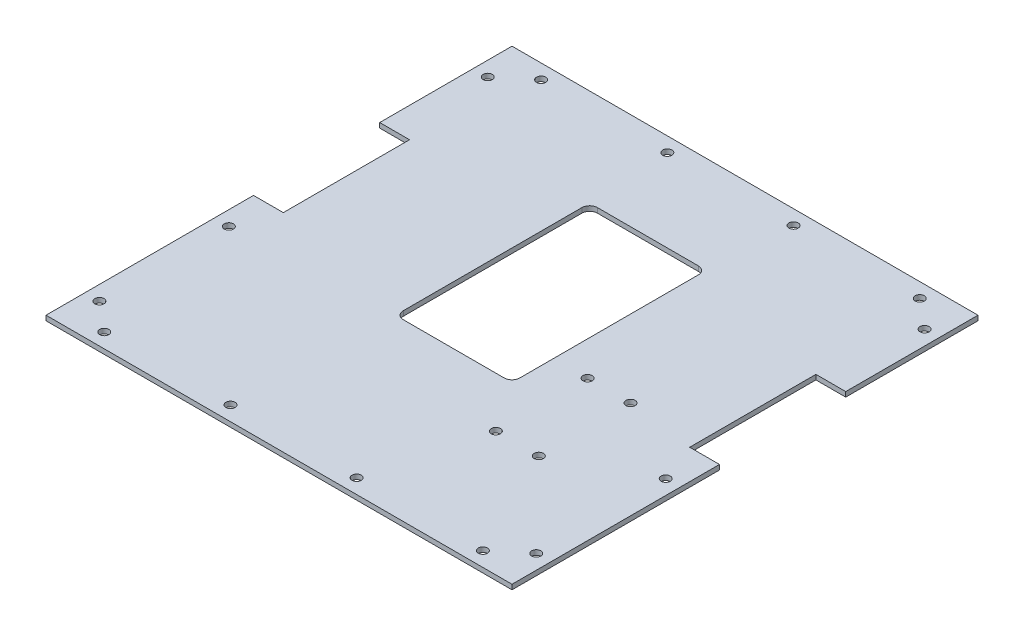
SolidWorks part; units mm, degrees
material "Thornel VCB-20 Carbon Cloth"
ref_plane "Front Plane" through (0, 0, 0) normal (0, 0, 1) x (1, 0, 0)
ref_plane "Top Plane" through (0, 0, 0) normal (0, 1, 0) x (1, 0, 0)
ref_plane "Right Plane" through (0, 0, 0) normal (1, 0, 0) x (0, 0, -1)
sketch "Sketch2" plane through (0, 0, 0) normal (0, 1, 0) x (1, 0, 0)
  line L0 (0, 0) -> (152.4, 0)
  line L1 (152.4, 0) -> (152.4, 152.4)
  line L2 (152.4, 152.4) -> (0, 152.4)
  line L3 (0, 152.4) -> (0, 0)
  dimension "D1" = 152.4
  dimension "D2" = 152.4
extrude "Boss-Extrude1" add sketch "Sketch2" along normal blind 1.5875
sketch "Sketch3" plane through (0, 1.5875, 0) normal (0, 1, 0) x (1, 0, 0)
  line L0 (0, 152.4) -> (4.7625, 152.4)
  line L1 (152.4, 152.4) -> (0, 152.4) construction
  line L2 (4.7625, 152.4) -> (4.7625, 0)
  line L3 (0, 0) -> (152.4, 0) construction
  line L4 (0, 152.4) -> (0, 147.6375)
  line L5 (0, 152.4) -> (0, 0) construction
  line L6 (0, 147.6375) -> (152.4, 147.6375)
  line L7 (152.4, 0) -> (152.4, 152.4) construction
  line L8 (152.4, 152.4) -> (147.6375, 152.4)
  line L9 (147.6375, 152.4) -> (147.6375, 0)
  line L10 (152.4, 0) -> (152.4, 4.7625)
  line L11 (152.4, 4.7625) -> (0, 4.7625)
  point P21 (4.7625, 139.7)
  point P23 (14.2875, 147.6375)
  point P24 (147.6375, 139.7)
  point P25 (138.1125, 4.7625)
  point P26 (4.7625, 12.7)
  dimension "D1" = 4.7625
  dimension "D2" = 4.7625
  dimension "D3" = 4.7625
  dimension "D4" = 4.7625
  dimension "D5" = 12.7
  dimension "D6" = 14.2875
  dimension "D7" = 12.7
  dimension "D8" = 14.2875
  dimension "D9" = 12.7
sketch "Sketch4" plane through (0, 1.5875, 0) normal (0, 1, 0) x (1, 0, 0)
  point P0 (14.2875, 147.6375)
  point P3 (147.6375, 139.7)
  point P6 (138.1125, 4.7625)
  point P9 (4.7625, 12.7)
sketch "Sketch6" plane through (0, 1.5875, 0) normal (0, 1, 0) x (1, 0, 0)
  line L0 (152.4, 4.7625) -> (0, 4.7625) construction
  line L1 (0, 152.4) -> (0, 0) construction
  point P0 (14.2875, 147.6375)
  point P3 (14.2875, 4.7625)
  dimension "D1" = 14.2875
hole_wizard "Ø3.0mm Dowel Hole1" positions "Sketch6" profile "Sketch7" hole size "Ø3.0" standard "ANSI Metric" end condition through all
sketch "Sketch7" plane through (14.2875, 1.5875, -147.6375) normal (1, 0, 0) x (0, 0, 1)
  line L0 (0, 0) -> (0, 1.5875)
  line L1 (0, 1.5875) -> (1.5, 1.5875)
  line L2 (1.5, 1.5875) -> (1.5, 0)
  line L5 (1.5, 0) -> (0, 0)
  line L11 (0, -6.35) -> (0, 107.95) construction
  dimension "Thru Hole Dia." = 3
  dimension "Thru Hole Depth" = 1.5875
sketch "Sketch8" plane through (0, 1.5875, 0) normal (0, 1, 0) x (1, 0, 0)
  point P0 (4.7625, 139.7)
  point P3 (147.6375, 139.7)
hole_wizard "Ø3.0mm Dowel Hole2" positions "Sketch8" profile "Sketch9" hole size "Ø3.0" standard "ANSI Metric" end condition through all
sketch "Sketch9" plane through (4.7625, 1.5875, -139.7) normal (1, 0, 0) x (0, 0, 1)
  line L0 (0, 0) -> (0, 1.5875)
  line L1 (0, 1.5875) -> (1.5, 1.5875)
  line L2 (1.5, 1.5875) -> (1.5, 0)
  line L5 (1.5, 0) -> (0, 0)
  line L11 (0, -6.35) -> (0, 107.95) construction
  dimension "Thru Hole Dia." = 3
  dimension "Thru Hole Depth" = 1.5875
pattern_linear "LPattern1" count 4 spacing 42.3333 along (0, 0, 1) skipping (1, 0) of "Ø3.0mm Dowel Hole2"
pattern_linear "LPattern2" count 4 spacing 41.275 along (1, 0, 0) of "Ø3.0mm Dowel Hole1"
sketch "Sketch12" plane through (0, 1.5875, 0) normal (0, 1, 0) x (1, 0, 0)
  line L10 (0, 152.4) -> (0, 0) construction
  line L11 (57.15, 120.65) -> (95.25, 120.65)
  line L12 (57.15, 120.65) -> (57.15, 57.15)
  line L13 (57.15, 57.15) -> (95.25, 57.15)
  line L14 (95.25, 120.65) -> (95.25, 57.15)
  line L15 (152.4, 152.4) -> (0, 152.4) construction
  line L16 (152.4, 0) -> (152.4, 152.4) construction
  dimension "D1" = 57.15
  dimension "D2" = 31.75
  dimension "D3" = 57.15
  dimension "D4" = 63.5
extrude "Cut-Extrude1" cut sketch "Sketch12" against normal blind 2.54
fillet "Fillet2" radius 2.54 4 edges at (95.25, 0.7937, -57.15) (57.15, 0.7937, -57.15) (57.15, 0.7937, -120.65) (95.25, 0.7937, -120.65)
sketch "Sketch13" plane through (0, 1.5875, 0) normal (0, 1, 0) x (1, 0, 0)
  line L0 (152.4, 0) -> (152.4, 152.4) construction
  line L1 (152.4, 109.14) -> (142.65, 109.14)
  line L2 (152.4, 109.14) -> (152.4, 67.86)
  line L3 (152.4, 67.86) -> (142.65, 67.86)
  line L4 (142.65, 109.14) -> (142.65, 67.86)
  line L5 (152.4, 152.4) -> (0, 152.4) construction
  line L6 (76.2, 152.4) -> (76.2, 0) construction
  line L7 (0, 0) -> (152.4, 0) construction
  line L8 (0, 67.86) -> (9.75, 67.86)
  line L9 (9.75, 109.14) -> (9.75, 67.86)
  line L10 (0, 109.14) -> (9.75, 109.14)
  line L11 (0, 109.14) -> (0, 67.86)
  point P8 (147.525, 67.86)
  dimension "D1" = 43.26
  dimension "D2" = 41.28
  dimension "D3" = 9.75
extrude "Cut-Extrude2" cut sketch "Sketch13" against normal through all
sketch "Sketch14" plane through (0, 0, 0) normal (0, -1, 0) x (1, 0, 0)
  circle A0 centre (120.4506, -70.7194) radius 1.5
  circle A1 centre (106.4006, -70.7194) radius 1.5
  circle A2 centre (120.4506, -40.7194) radius 1.5
  circle A3 centre (106.4006, -40.7194) radius 1.5
extrude "Cut-Extrude3" cut sketch "Sketch14" against normal blind 10 contours A2 | A3 | A1 | A0
